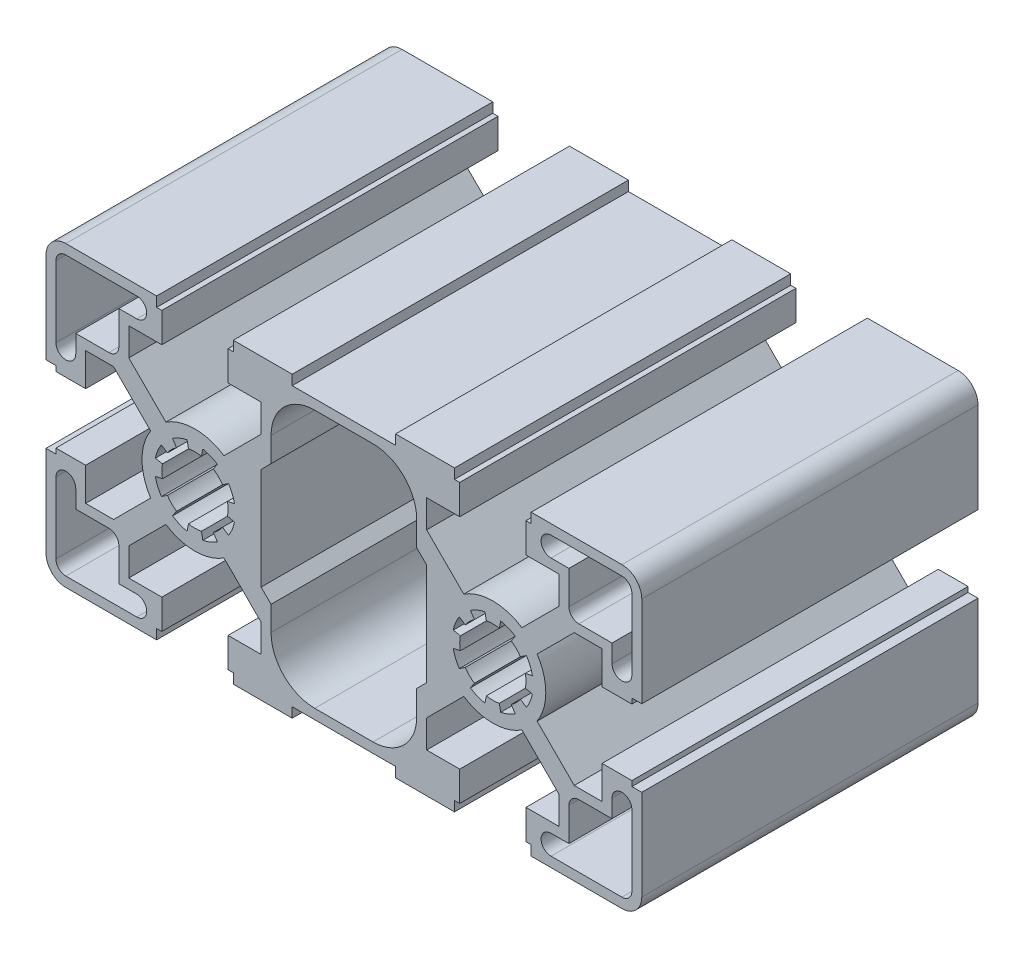
SolidWorks part; units mm, degrees
ref_plane "Front Plane" through (0, 0, 0) normal (0, 0, 1) x (1, 0, 0)
ref_plane "Top Plane" through (0, 0, 0) normal (0, 1, 0) x (1, 0, 0)
ref_plane "Right Plane" through (0, 0, 0) normal (1, 0, 0) x (0, 0, -1)
sketch "Sketch1" plane through (0, 0, 0) normal (0, 0, 1) x (1, 0, 0)
  line L0 (0, 22.5044) -> (0, -22.5044) construction
  line L1 (-22.5044, 0) -> (-22.5044, 22.5044) construction
  line L2 (-19.5072, 22.5044) -> (-5.7912, 22.5044)
  line L3 (-5.7912, 22.5044) -> (-5.7912, 21.0058)
  line L4 (-5.7912, 21.0058) -> (-5.0038, 21.0058)
  line L5 (-22.5044, 0) -> (22.5044, 0) construction
  line L6 (-5.0038, 21.0058) -> (-5.0038, 16.51)
  line L7 (-5.0038, 16.51) -> (-10, 16.51)
  line L8 (-10, 16.51) -> (-10, 12.2989)
  line L9 (-10, 12.2989) -> (-4.3901, 6.689)
  line L10 (0, 0) -> (-19.5072, 19.5072) construction
  line L11 (-12.2989, 10) -> (-6.689, 4.3901)
  line L12 (-16.51, 10) -> (-12.2989, 10)
  line L13 (-16.51, 5.0038) -> (-16.51, 10)
  line L14 (-21.0058, 5.0038) -> (-16.51, 5.0038)
  line L15 (-21.0058, 5.7912) -> (-21.0058, 5.0038)
  line L16 (-22.5044, 5.7912) -> (-21.0058, 5.7912)
  line L17 (-22.5044, 19.5072) -> (-22.5044, 5.7912)
  line L18 (-18.0086, 11.4986) -> (-12.9972, 11.4986)
  line L19 (-18.0086, 11.4986) -> (-18.0086, 8.7884)
  line L20 (-11.4986, 18.0086) -> (-11.4986, 12.9972)
  line L21 (-21.0058, 19.5072) -> (-21.0058, 8.7884)
  line L22 (-22.5044, 7.2898) -> (-21.0058, 7.2898) construction
  line L23 (-11.4986, 18.0086) -> (-8.7884, 18.0086)
  line L24 (-19.5072, 21.0058) -> (-8.7884, 21.0058)
  line L25 (1.1893, 5.9789) -> (0.9762, 4.9077)
  line L26 (-1.1893, 5.9789) -> (-0.9762, 4.9077)
  line L27 (5.0686, 3.3868) -> (4.1605, 2.78)
  line L28 (3.3868, 5.0686) -> (2.78, 4.1605)
  line L29 (5.9789, -1.1893) -> (4.9077, -0.9762)
  line L30 (5.9789, 1.1893) -> (4.9077, 0.9762)
  line L31 (3.3868, -5.0686) -> (2.78, -4.1605)
  line L32 (5.0686, -3.3868) -> (4.1605, -2.78)
  line L33 (-1.1893, -5.9789) -> (-0.9762, -4.9077)
  line L34 (1.1893, -5.9789) -> (0.9762, -4.9077)
  line L35 (-5.0686, -3.3868) -> (-4.1605, -2.78)
  line L36 (-3.3868, -5.0686) -> (-2.78, -4.1605)
  line L37 (-5.9789, 1.1893) -> (-4.9077, 0.9762)
  line L38 (-5.9789, -1.1893) -> (-4.9077, -0.9762)
  line L39 (-3.3868, 5.0686) -> (-2.78, 4.1605)
  line L40 (-5.0686, 3.3868) -> (-4.1605, 2.78)
  line L41 (14.6939, 22.5044) -> (14.6939, 21.0058)
  line L42 (14.6939, 21.0058) -> (30.3149, 21.0058)
  line L43 (14.6939, 22.5044) -> (5.7912, 22.5044)
  line L44 (5.7912, 22.5044) -> (5.7912, 21.0058)
  line L45 (5.7912, 21.0058) -> (5.0038, 21.0058)
  line L46 (5.0038, 21.0058) -> (5.0038, 16.51)
  line L47 (5.0038, 16.51) -> (10, 16.51)
  line L48 (10, 16.51) -> (10, 12.2989)
  line L49 (10, 12.2989) -> (4.3901, 6.689)
  line L50 (11.4986, 9.1997) -> (10, 7.7011)
  line L51 (30.3149, 21.0058) -> (30.3149, 22.5044)
  line L52 (22.5044, 5.7912) -> (22.5044, 21.0058) construction
  line L53 (14.6939, -22.5044) -> (5.7912, -22.5044)
  line L54 (30.3149, -22.5044) -> (39.2176, -22.5044)
  line L55 (30.3149, -21.0058) -> (30.3149, -22.5044)
  line L56 (14.6939, -21.0058) -> (30.3149, -21.0058)
  line L57 (14.6939, -22.5044) -> (14.6939, -21.0058)
  line L58 (-18.0086, -11.4986) -> (-12.9972, -11.4986)
  line L59 (26.9062, 19.5072) -> (18.1026, 19.5072)
  line L60 (11.4986, 12.9032) -> (11.4986, 9.1997)
  line L61 (10, -7.7011) -> (11.4986, -9.1997)
  line L62 (10, 7.7011) -> (10, -7.7011)
  line L63 (11.4986, -12.9032) -> (11.4986, -9.1997)
  line L64 (26.9062, -19.5072) -> (18.1026, -19.5072)
  line L65 (33.5102, 12.9032) -> (33.5102, 9.1997)
  line L66 (33.5102, -12.9032) -> (33.5102, -9.1997)
  line L67 (35.0088, 7.7011) -> (35.0088, -7.7011)
  line L68 (33.5102, -9.1997) -> (35.0088, -7.7011)
  line L69 (33.5102, 9.1997) -> (35.0088, 7.7011)
  line L72 (10, -12.2989) -> (4.3901, -6.689)
  line L73 (10, -16.51) -> (10, -12.2989)
  line L74 (5.0038, -16.51) -> (10, -16.51)
  line L75 (5.0038, -21.0058) -> (5.0038, -16.51)
  line L76 (5.7912, -21.0058) -> (5.0038, -21.0058)
  line L77 (5.7912, -22.5044) -> (5.7912, -21.0058)
  line L81 (-11.4986, -18.0086) -> (-8.7884, -18.0086)
  line L82 (-19.5072, -21.0058) -> (-8.7884, -21.0058)
  line L83 (-19.5072, -22.5044) -> (-5.7912, -22.5044)
  line L84 (-5.7912, -22.5044) -> (-5.7912, -21.0058)
  line L85 (-5.7912, -21.0058) -> (-5.0038, -21.0058)
  line L86 (-5.0038, -21.0058) -> (-5.0038, -16.51)
  line L87 (-5.0038, -16.51) -> (-10, -16.51)
  line L88 (-10, -16.51) -> (-10, -12.2989)
  line L89 (-10, -12.2989) -> (-4.3901, -6.689)
  line L90 (-12.2989, -10) -> (-6.689, -4.3901)
  line L91 (-21.0058, -19.5072) -> (-21.0058, -8.7884)
  line L92 (-11.4986, -18.0086) -> (-11.4986, -12.9972)
  line L93 (-18.0086, -11.4986) -> (-18.0086, -8.7884)
  line L95 (-22.5044, -19.5072) -> (-22.5044, -5.7912)
  line L96 (-22.5044, -5.7912) -> (-21.0058, -5.7912)
  line L97 (-21.0058, -5.7912) -> (-21.0058, -5.0038)
  line L98 (-21.0058, -5.0038) -> (-16.51, -5.0038)
  line L99 (-16.51, -5.0038) -> (-16.51, -10)
  line L100 (-16.51, -10) -> (-12.2989, -10)
  line L101 (22.5044, -5.7912) -> (22.5044, 5.7912) construction
  line L102 (64.516, 21.0058) -> (53.7972, 21.0058)
  line L103 (64.516, 22.5044) -> (50.8, 22.5044)
  line L104 (56.5074, 18.0086) -> (53.7972, 18.0086)
  line L105 (50.0126, 21.0058) -> (50.0126, 16.51)
  line L106 (50.8, 21.0058) -> (50.0126, 21.0058)
  line L107 (50.8, 22.5044) -> (50.8, 21.0058)
  line L109 (40.005, 21.0058) -> (40.005, 16.51)
  line L110 (39.2176, 21.0058) -> (40.005, 21.0058)
  line L111 (39.2176, 22.5044) -> (39.2176, 21.0058)
  line L112 (30.3149, 22.5044) -> (39.2176, 22.5044)
  line L114 (61.5188, -10) -> (57.3077, -10)
  line L115 (61.5188, -5.0038) -> (61.5188, -10)
  line L116 (66.0146, -5.0038) -> (61.5188, -5.0038)
  line L117 (66.0146, -5.7912) -> (66.0146, -5.0038)
  line L118 (67.5132, -5.7912) -> (66.0146, -5.7912)
  line L119 (67.5132, -19.5072) -> (67.5132, -5.7912)
  line L120 (63.0174, -11.4986) -> (58.006, -11.4986)
  line L121 (63.0174, -11.4986) -> (63.0174, -8.7884)
  line L122 (56.5074, -18.0086) -> (56.5074, -12.9972)
  line L123 (66.0146, -19.5072) -> (66.0146, -8.7884)
  line L124 (57.3077, -10) -> (51.6978, -4.3901)
  line L125 (55.0088, -12.2989) -> (49.3989, -6.689)
  line L126 (55.0088, -16.51) -> (55.0088, -12.2989)
  line L127 (50.0126, -16.51) -> (55.0088, -16.51)
  line L128 (50.0126, -21.0058) -> (50.0126, -16.51)
  line L129 (50.8, -21.0058) -> (50.0126, -21.0058)
  line L130 (50.8, -22.5044) -> (50.8, -21.0058)
  line L131 (64.516, -22.5044) -> (50.8, -22.5044)
  line L132 (64.516, -21.0058) -> (53.7972, -21.0058)
  line L133 (56.5074, -18.0086) -> (53.7972, -18.0086)
  line L137 (39.2176, -22.5044) -> (39.2176, -21.0058)
  line L138 (39.2176, -21.0058) -> (40.005, -21.0058)
  line L139 (40.005, -21.0058) -> (40.005, -16.51)
  line L140 (40.005, -16.51) -> (35.0088, -16.51)
  line L141 (35.0088, -16.51) -> (35.0088, -12.2989)
  line L142 (35.0088, -12.2989) -> (40.6187, -6.689)
  line L155 (35.0088, 12.2989) -> (40.6187, 6.689)
  line L156 (35.0088, 16.51) -> (35.0088, 12.2989)
  line L157 (50.0774, 3.3868) -> (49.1693, 2.78)
  line L158 (48.3956, 5.0686) -> (47.7888, 4.1605)
  line L159 (50.9877, -1.1893) -> (49.9165, -0.9762)
  line L160 (50.9877, 1.1893) -> (49.9165, 0.9762)
  line L161 (48.3956, -5.0686) -> (47.7888, -4.1605)
  line L162 (50.0774, -3.3868) -> (49.1693, -2.78)
  line L163 (43.8195, -5.9789) -> (44.0326, -4.9077)
  line L164 (46.1981, -5.9789) -> (45.985, -4.9077)
  line L165 (39.9402, -3.3868) -> (40.8483, -2.78)
  line L166 (41.622, -5.0686) -> (42.2288, -4.1605)
  line L167 (39.0299, 1.1893) -> (40.1011, 0.9762)
  line L168 (39.0299, -1.1893) -> (40.1011, -0.9762)
  line L169 (41.622, 5.0686) -> (42.2288, 4.1605)
  line L170 (39.9402, 3.3868) -> (40.8483, 2.78)
  line L171 (46.1981, 5.9789) -> (45.985, 4.9077)
  line L172 (43.8195, 5.9789) -> (44.0326, 4.9077)
  line L173 (66.0146, 19.5072) -> (66.0146, 8.7884)
  line L174 (56.5074, 18.0086) -> (56.5074, 12.9972)
  line L175 (63.0174, 11.4986) -> (63.0174, 8.7884)
  line L176 (63.0174, 11.4986) -> (58.006, 11.4986)
  line L177 (67.5132, 19.5072) -> (67.5132, 5.7912)
  line L178 (67.5132, 5.7912) -> (66.0146, 5.7912)
  line L179 (66.0146, 5.7912) -> (66.0146, 5.0038)
  line L180 (66.0146, 5.0038) -> (61.5188, 5.0038)
  line L181 (61.5188, 5.0038) -> (61.5188, 10)
  line L182 (61.5188, 10) -> (57.3077, 10)
  line L183 (57.3077, 10) -> (51.6978, 4.3901)
  line L184 (55.0088, 12.2989) -> (49.3989, 6.689)
  line L185 (55.0088, 16.51) -> (55.0088, 12.2989)
  line L186 (35.0088, 16.51) -> (40.005, 16.51)
  line L187 (50.0126, 16.51) -> (55.0088, 16.51)
  arc A0 (-22.5044, 19.5072) -> (-19.5072, 22.5044) centre (-19.5072, 19.5072) cw
  arc A1 (-21.0058, 8.7884) -> (-18.0086, 8.7884) centre (-19.5072, 8.7884) ccw
  arc A2 (-21.0058, 19.5072) -> (-19.5072, 21.0058) centre (-19.5072, 19.5072) cw
  arc A3 (-8.7884, 21.0058) -> (-8.7884, 18.0086) centre (-8.7884, 19.5072) cw
  arc A4 (-11.4986, 12.9972) -> (-12.9972, 11.4986) centre (-12.9972, 12.9972) cw
  arc A5 (6.689, -4.3901) -> (8.001, 0) centre (0, 0) ccw construction
  arc A6 (0.9762, 4.9077) -> (-0.9762, 4.9077) centre (0, 0) ccw
  arc A7 (-5.0686, 3.3868) -> (-5.9789, 1.1893) centre (0, 0) ccw
  arc A8 (4.1605, 2.78) -> (2.78, 4.1605) centre (0, 0) ccw
  arc A9 (4.9077, -0.9762) -> (4.9077, 0.9762) centre (0, 0) ccw
  arc A10 (2.78, -4.1605) -> (4.1605, -2.78) centre (0, 0) ccw
  arc A11 (-0.9762, -4.9077) -> (0.9762, -4.9077) centre (0, 0) ccw
  arc A12 (-4.1605, -2.78) -> (-2.78, -4.1605) centre (0, 0) ccw
  arc A13 (-4.9077, 0.9762) -> (-4.9077, -0.9762) centre (0, 0) ccw
  arc A14 (-2.78, 4.1605) -> (-4.1605, 2.78) centre (0, 0) ccw
  arc A15 (-5.9789, -1.1893) -> (-5.0686, -3.3868) centre (0, 0) ccw
  arc A16 (-3.3868, -5.0686) -> (-1.1893, -5.9789) centre (0, 0) ccw
  arc A17 (1.1893, -5.9789) -> (3.3868, -5.0686) centre (0, 0) ccw
  arc A18 (5.0686, -3.3868) -> (5.9789, -1.1893) centre (0, 0) ccw
  arc A19 (5.9789, 1.1893) -> (5.0686, 3.3868) centre (0, 0) ccw
  arc A20 (3.3868, 5.0686) -> (1.1893, 5.9789) centre (0, 0) ccw
  arc A21 (-1.1893, 5.9789) -> (-3.3868, 5.0686) centre (0, 0) ccw
  arc A22 (-11.4986, -12.9972) -> (-12.9972, -11.4986) centre (-12.9972, -12.9972) ccw
  arc A23 (18.1026, 19.5072) -> (11.4986, 12.9032) centre (18.1026, 12.9032) ccw
  arc A24 (18.1026, -19.5072) -> (11.4986, -12.9032) centre (18.1026, -12.9032) cw
  arc A25 (26.9062, 19.5072) -> (33.5102, 12.9032) centre (26.9062, 12.9032) cw
  arc A26 (26.9062, -19.5072) -> (33.5102, -12.9032) centre (26.9062, -12.9032) ccw
  arc A32 (-8.7884, -21.0058) -> (-8.7884, -18.0086) centre (-8.7884, -19.5072) ccw
  arc A33 (-21.0058, -19.5072) -> (-19.5072, -21.0058) centre (-19.5072, -19.5072) ccw
  arc A34 (-22.5044, -19.5072) -> (-19.5072, -22.5044) centre (-19.5072, -19.5072) ccw
  arc A36 (-21.0058, -8.7884) -> (-18.0086, -8.7884) centre (-19.5072, -8.7884) cw
  arc A37 (4.3901, 6.689) -> (-4.3901, 6.689) centre (0, 0) ccw
  arc A38 (-4.3901, -6.689) -> (4.3901, -6.689) centre (0, 0) ccw
  arc A39 (-6.689, 4.3901) -> (-6.689, -4.3901) centre (0, 0) ccw
  arc A40 (67.5132, 19.5072) -> (64.516, 22.5044) centre (64.516, 19.5072) ccw
  arc A41 (66.0146, 19.5072) -> (64.516, 21.0058) centre (64.516, 19.5072) ccw
  arc A42 (53.7972, 21.0058) -> (53.7972, 18.0086) centre (53.7972, 19.5072) ccw
  arc A44 (51.6978, 4.3901) -> (51.6978, -4.3901) centre (45.0088, 0) cw
  arc A45 (49.3989, -6.689) -> (40.6187, -6.689) centre (45.0088, 0) cw
  arc A46 (40.6187, 6.689) -> (49.3989, 6.689) centre (45.0088, 0) cw
  arc A47 (66.0146, -8.7884) -> (63.0174, -8.7884) centre (64.516, -8.7884) ccw
  arc A48 (56.5074, -12.9972) -> (58.006, -11.4986) centre (58.006, -12.9972) cw
  arc A49 (67.5132, -19.5072) -> (64.516, -22.5044) centre (64.516, -19.5072) cw
  arc A50 (66.0146, -19.5072) -> (64.516, -21.0058) centre (64.516, -19.5072) cw
  arc A51 (53.7972, -21.0058) -> (53.7972, -18.0086) centre (53.7972, -19.5072) cw
  arc A55 (46.1981, 5.9789) -> (48.3956, 5.0686) centre (45.0088, 0) cw
  arc A56 (41.622, 5.0686) -> (43.8195, 5.9789) centre (45.0088, 0) cw
  arc A57 (39.0299, 1.1893) -> (39.9402, 3.3868) centre (45.0088, 0) cw
  arc A58 (39.9402, -3.3868) -> (39.0299, -1.1893) centre (45.0088, 0) cw
  arc A59 (43.8195, -5.9789) -> (41.622, -5.0686) centre (45.0088, 0) cw
  arc A60 (48.3956, -5.0686) -> (46.1981, -5.9789) centre (45.0088, 0) cw
  arc A61 (50.9877, -1.1893) -> (50.0774, -3.3868) centre (45.0088, 0) cw
  arc A62 (47.7888, 4.1605) -> (49.1693, 2.78) centre (45.0088, 0) cw
  arc A63 (49.9165, 0.9762) -> (49.9165, -0.9762) centre (45.0088, 0) cw
  arc A64 (49.1693, -2.78) -> (47.7888, -4.1605) centre (45.0088, 0) cw
  arc A65 (45.985, -4.9077) -> (44.0326, -4.9077) centre (45.0088, 0) cw
  arc A66 (42.2288, -4.1605) -> (40.8483, -2.78) centre (45.0088, 0) cw
  arc A67 (40.1011, -0.9762) -> (40.1011, 0.9762) centre (45.0088, 0) cw
  arc A68 (40.8483, 2.78) -> (42.2288, 4.1605) centre (45.0088, 0) cw
  arc A69 (50.0774, 3.3868) -> (50.9877, 1.1893) centre (45.0088, 0) cw
  arc A70 (44.0326, 4.9077) -> (45.985, 4.9077) centre (45.0088, 0) cw
  arc A71 (38.3198, -4.3901) -> (38.5934, 4.781) centre (45.0088, 0) cw construction
  arc A72 (56.5074, 12.9972) -> (58.006, 11.4986) centre (58.006, 12.9972) ccw
  arc A73 (66.0146, 8.7884) -> (63.0174, 8.7884) centre (64.516, 8.7884) cw
  point P84 (22.5044, -19.5072)
  point P112 (22.5044, 19.5072)
  dimension "D3" = 2.9972
  dimension "D12" = 1.4986
  dimension "D13" = 1.4986
  dimension "D14" = 16.002
  dimension "D15" = 10.0076
  dimension "D16" = 12.192
  dimension "D21" = 6.604
  dimension "D1" = 45.0088
  dimension "D2" = 1.4986
  dimension "D4" = 0.7874
  dimension "D5" = 3.2512
  dimension "D6" = 17.5006
  dimension "D7" = 1.4986
  dimension "D8" = 20
  dimension "D9" = 5.9944
  dimension "D10" = 1.4986
  dimension "D11" = 1.4986
  dimension "D17" = 22.5
  dimension "D18" = 11.25
  dimension "D19" = 15.621
  dimension "D20" = 1.4986
  dimension "D22" = 1.4986
extrude "Extrude1" add sketch "Sketch1" along normal mid plane 50.8
equation "\"D2@Sketch1\" = \"D7@Sketch1\""
equation "\"D11@Sketch1\" = \"D7@Sketch1\""
equation "\"D10@Sketch1\" = \"D7@Sketch1\""
equation "\"D12@Sketch1\" = \"D7@Sketch1\""
equation "\"D13@Sketch1\" = \"D7@Sketch1\""
equation "\"D18@Sketch1\" = \"D17@Sketch1\"/2"
